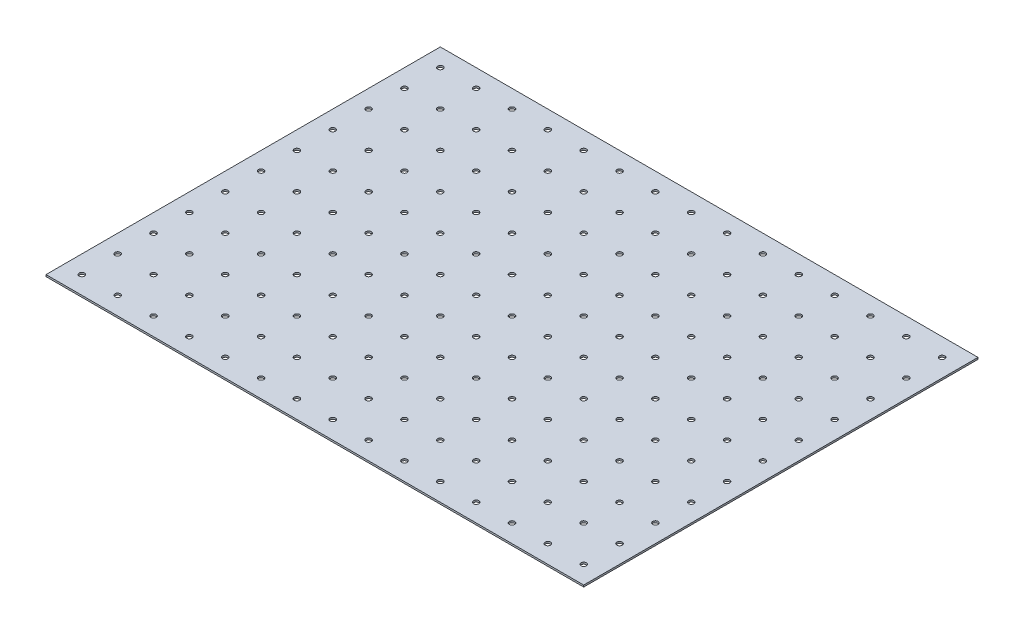
SolidWorks part; units mm, degrees
ref_plane "Front Plane" through (0, 0, 0) normal (0, 0, 1) x (1, 0, 0)
ref_plane "Top Plane" through (0, 0, 0) normal (0, 1, 0) x (1, 0, 0)
ref_plane "Right Plane" through (0, 0, 0) normal (1, 0, 0) x (0, 0, -1)
sketch "Sketch1" plane through (0, 0, 0) normal (0, 1, 0) x (1, 0, 0)
  line L1 (0, 0) -> (-300, 0)
  line L2 (0, 0) -> (0, 220)
  line L3 (0, 220) -> (-300, 220)
  line L4 (-300, 0) -> (-300, 220)
extrude "Boss-Extrude1" add sketch "Sketch1" along normal blind 1
sketch "Sketch2" plane through (0, 1, 0) normal (0, 1, 0) x (1, 0, 0)
  line L0 (-300, 220) -> (-300, 0) construction
  line L1 (0, 220) -> (-300, 220) construction
  line L2 (-280, 220) -> (-280, 0) construction
  line L3 (-300, 0) -> (0, 0) construction
  line L4 (-300, 200) -> (0, 200) construction
  line L5 (0, 0) -> (0, 220) construction
  line L6 (-280, 200) -> (-280, -20) construction
  line L7 (-280, 180) -> (-280, -40) construction
  line L8 (-280, 160) -> (-280, -60) construction
  line L9 (-280, 140) -> (-280, -80) construction
  line L10 (-280, 120) -> (-280, -100) construction
  line L11 (-280, 100) -> (-280, -120) construction
  line L12 (-280, 80) -> (-280, -140) construction
  line L13 (-280, 60) -> (-280, -160) construction
  line L14 (-280, 40) -> (-280, -180) construction
  line L15 (-280, 20) -> (-280, -200) construction
  circle A0 centre (-290, 210) radius 1.5
  circle A1 centre (-270, 210) radius 1.5
  circle A2 centre (-250, 210) radius 1.5
  circle A3 centre (-230, 210) radius 1.5
  circle A4 centre (-210, 210) radius 1.5
  circle A5 centre (-190, 210) radius 1.5
  circle A6 centre (-170, 210) radius 1.5
  circle A7 centre (-150, 210) radius 1.5
  circle A8 centre (-130, 210) radius 1.5
  circle A9 centre (-110, 210) radius 1.5
  circle A10 centre (-90, 210) radius 1.5
  circle A11 centre (-70, 210) radius 1.5
  circle A12 centre (-50, 210) radius 1.5
  circle A13 centre (-30, 210) radius 1.5
  circle A14 centre (-10, 210) radius 1.5
  circle A15 centre (-290, 190) radius 1.5
  circle A16 centre (-270, 190) radius 1.5
  circle A17 centre (-250, 190) radius 1.5
  circle A18 centre (-230, 190) radius 1.5
  circle A19 centre (-210, 190) radius 1.5
  circle A20 centre (-190, 190) radius 1.5
  circle A21 centre (-170, 190) radius 1.5
  circle A22 centre (-150, 190) radius 1.5
  circle A23 centre (-130, 190) radius 1.5
  circle A24 centre (-110, 190) radius 1.5
  circle A25 centre (-90, 190) radius 1.5
  circle A26 centre (-70, 190) radius 1.5
  circle A27 centre (-50, 190) radius 1.5
  circle A28 centre (-30, 190) radius 1.5
  circle A29 centre (-10, 190) radius 1.5
  circle A30 centre (-290, 170) radius 1.5
  circle A31 centre (-270, 170) radius 1.5
  circle A32 centre (-250, 170) radius 1.5
  circle A33 centre (-230, 170) radius 1.5
  circle A34 centre (-210, 170) radius 1.5
  circle A35 centre (-190, 170) radius 1.5
  circle A36 centre (-170, 170) radius 1.5
  circle A37 centre (-150, 170) radius 1.5
  circle A38 centre (-130, 170) radius 1.5
  circle A39 centre (-110, 170) radius 1.5
  circle A40 centre (-90, 170) radius 1.5
  circle A41 centre (-70, 170) radius 1.5
  circle A42 centre (-50, 170) radius 1.5
  circle A43 centre (-30, 170) radius 1.5
  circle A44 centre (-10, 170) radius 1.5
  circle A45 centre (-290, 150) radius 1.5
  circle A46 centre (-270, 150) radius 1.5
  circle A47 centre (-250, 150) radius 1.5
  circle A48 centre (-230, 150) radius 1.5
  circle A49 centre (-210, 150) radius 1.5
  circle A50 centre (-190, 150) radius 1.5
  circle A51 centre (-170, 150) radius 1.5
  circle A52 centre (-150, 150) radius 1.5
  circle A53 centre (-130, 150) radius 1.5
  circle A54 centre (-110, 150) radius 1.5
  circle A55 centre (-90, 150) radius 1.5
  circle A56 centre (-70, 150) radius 1.5
  circle A57 centre (-50, 150) radius 1.5
  circle A58 centre (-30, 150) radius 1.5
  circle A59 centre (-10, 150) radius 1.5
  circle A60 centre (-290, 130) radius 1.5
  circle A61 centre (-270, 130) radius 1.5
  circle A62 centre (-250, 130) radius 1.5
  circle A63 centre (-230, 130) radius 1.5
  circle A64 centre (-210, 130) radius 1.5
  circle A65 centre (-190, 130) radius 1.5
  circle A66 centre (-170, 130) radius 1.5
  circle A67 centre (-150, 130) radius 1.5
  circle A68 centre (-130, 130) radius 1.5
  circle A69 centre (-110, 130) radius 1.5
  circle A70 centre (-90, 130) radius 1.5
  circle A71 centre (-70, 130) radius 1.5
  circle A72 centre (-50, 130) radius 1.5
  circle A73 centre (-30, 130) radius 1.5
  circle A74 centre (-10, 130) radius 1.5
  circle A75 centre (-290, 110) radius 1.5
  circle A76 centre (-270, 110) radius 1.5
  circle A77 centre (-250, 110) radius 1.5
  circle A78 centre (-230, 110) radius 1.5
  circle A79 centre (-210, 110) radius 1.5
  circle A80 centre (-190, 110) radius 1.5
  circle A81 centre (-170, 110) radius 1.5
  circle A82 centre (-150, 110) radius 1.5
  circle A83 centre (-130, 110) radius 1.5
  circle A84 centre (-110, 110) radius 1.5
  circle A85 centre (-90, 110) radius 1.5
  circle A86 centre (-70, 110) radius 1.5
  circle A87 centre (-50, 110) radius 1.5
  circle A88 centre (-30, 110) radius 1.5
  circle A89 centre (-10, 110) radius 1.5
  circle A90 centre (-290, 90) radius 1.5
  circle A91 centre (-270, 90) radius 1.5
  circle A92 centre (-250, 90) radius 1.5
  circle A93 centre (-230, 90) radius 1.5
  circle A94 centre (-210, 90) radius 1.5
  circle A95 centre (-190, 90) radius 1.5
  circle A96 centre (-170, 90) radius 1.5
  circle A97 centre (-150, 90) radius 1.5
  circle A98 centre (-130, 90) radius 1.5
  circle A99 centre (-110, 90) radius 1.5
  circle A100 centre (-90, 90) radius 1.5
  circle A101 centre (-70, 90) radius 1.5
  circle A102 centre (-50, 90) radius 1.5
  circle A103 centre (-30, 90) radius 1.5
  circle A104 centre (-10, 90) radius 1.5
  circle A105 centre (-290, 70) radius 1.5
  circle A106 centre (-270, 70) radius 1.5
  circle A107 centre (-250, 70) radius 1.5
  circle A108 centre (-230, 70) radius 1.5
  circle A109 centre (-210, 70) radius 1.5
  circle A110 centre (-190, 70) radius 1.5
  circle A111 centre (-170, 70) radius 1.5
  circle A112 centre (-150, 70) radius 1.5
  circle A113 centre (-130, 70) radius 1.5
  circle A114 centre (-110, 70) radius 1.5
  circle A115 centre (-90, 70) radius 1.5
  circle A116 centre (-70, 70) radius 1.5
  circle A117 centre (-50, 70) radius 1.5
  circle A118 centre (-30, 70) radius 1.5
  circle A119 centre (-10, 70) radius 1.5
  circle A120 centre (-290, 50) radius 1.5
  circle A121 centre (-270, 50) radius 1.5
  circle A122 centre (-250, 50) radius 1.5
  circle A123 centre (-230, 50) radius 1.5
  circle A124 centre (-210, 50) radius 1.5
  circle A125 centre (-190, 50) radius 1.5
  circle A126 centre (-170, 50) radius 1.5
  circle A127 centre (-150, 50) radius 1.5
  circle A128 centre (-130, 50) radius 1.5
  circle A129 centre (-110, 50) radius 1.5
  circle A130 centre (-90, 50) radius 1.5
  circle A131 centre (-70, 50) radius 1.5
  circle A132 centre (-50, 50) radius 1.5
  circle A133 centre (-30, 50) radius 1.5
  circle A134 centre (-10, 50) radius 1.5
  circle A135 centre (-290, 30) radius 1.5
  circle A136 centre (-270, 30) radius 1.5
  circle A137 centre (-250, 30) radius 1.5
  circle A138 centre (-230, 30) radius 1.5
  circle A139 centre (-210, 30) radius 1.5
  circle A140 centre (-190, 30) radius 1.5
  circle A141 centre (-170, 30) radius 1.5
  circle A142 centre (-150, 30) radius 1.5
  circle A143 centre (-130, 30) radius 1.5
  circle A144 centre (-110, 30) radius 1.5
  circle A145 centre (-90, 30) radius 1.5
  circle A146 centre (-70, 30) radius 1.5
  circle A147 centre (-50, 30) radius 1.5
  circle A148 centre (-30, 30) radius 1.5
  circle A149 centre (-10, 30) radius 1.5
  circle A150 centre (-290, 10) radius 1.5
  circle A151 centre (-270, 10) radius 1.5
  circle A152 centre (-250, 10) radius 1.5
  circle A153 centre (-230, 10) radius 1.5
  circle A154 centre (-210, 10) radius 1.5
  circle A155 centre (-190, 10) radius 1.5
  circle A156 centre (-170, 10) radius 1.5
  circle A157 centre (-150, 10) radius 1.5
  circle A158 centre (-130, 10) radius 1.5
  circle A159 centre (-110, 10) radius 1.5
  circle A160 centre (-90, 10) radius 1.5
  circle A161 centre (-70, 10) radius 1.5
  circle A162 centre (-50, 10) radius 1.5
  circle A163 centre (-30, 10) radius 1.5
  circle A164 centre (-10, 10) radius 1.5
  dimension "D1" = 10
  dimension "D2" = 10
  dimension "D3" = 20
  dimension "D4" = 20
  dimension "D5" = 15
  dimension "D6" = 11
extrude "Cut-Extrude1" cut sketch "Sketch2" against normal blind 10
